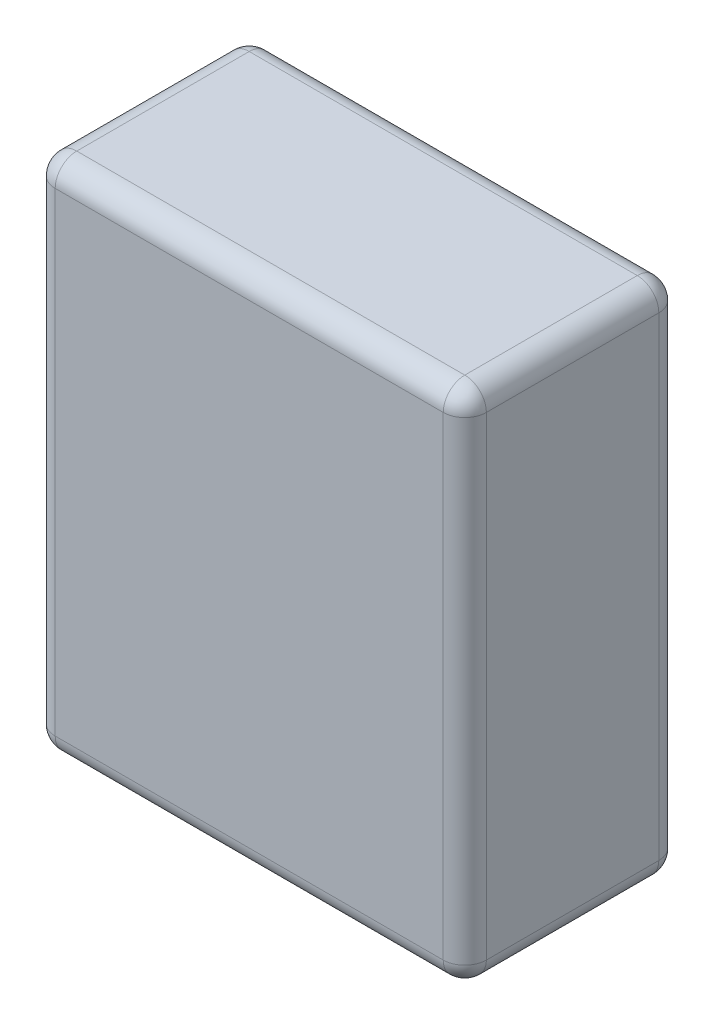
SolidWorks part; units mm, degrees
ref_plane "正面" through (0, 0, 0) normal (0, 0, 1) x (1, 0, 0)
ref_plane "平面" through (0, 0, 0) normal (0, 1, 0) x (1, 0, 0)
ref_plane "右側面" through (0, 0, 0) normal (1, 0, 0) x (0, 0, -1)
sketch "ｽｹｯﾁ1" plane through (0, 0, 0) normal (0, 0, 1) x (1, 0, 0)
  line L1 (-5, 6) -> (5, 6)
  line L2 (-5, 6) -> (-5, -6)
  line L3 (-5, -6) -> (5, -6)
  line L4 (5, 6) -> (5, -6)
  line L5 (0, -6) -> (0, 6) construction
  line L6 (-5, 0) -> (5, 0) construction
  point P0 (0, 0)
  dimension "D1" = 12
  dimension "D2" = 10
extrude "ﾎﾞｽ - 押し出し1" add sketch "ｽｹｯﾁ1" along normal blind 5
fillet "ﾌｨﾚｯﾄ1" radius 0.5 12 edges at (-5, -6, 2.5) (-5, 0, 0) (0, -6, 0) (5, -6, 2.5) (5, 0, 0) (0, -6, 5) (-5, 0, 5) (5, 0, 5) (5, 6, 2.5) (0, 6, 5) (-5, 6, 2.5) (0, 6, 0)
